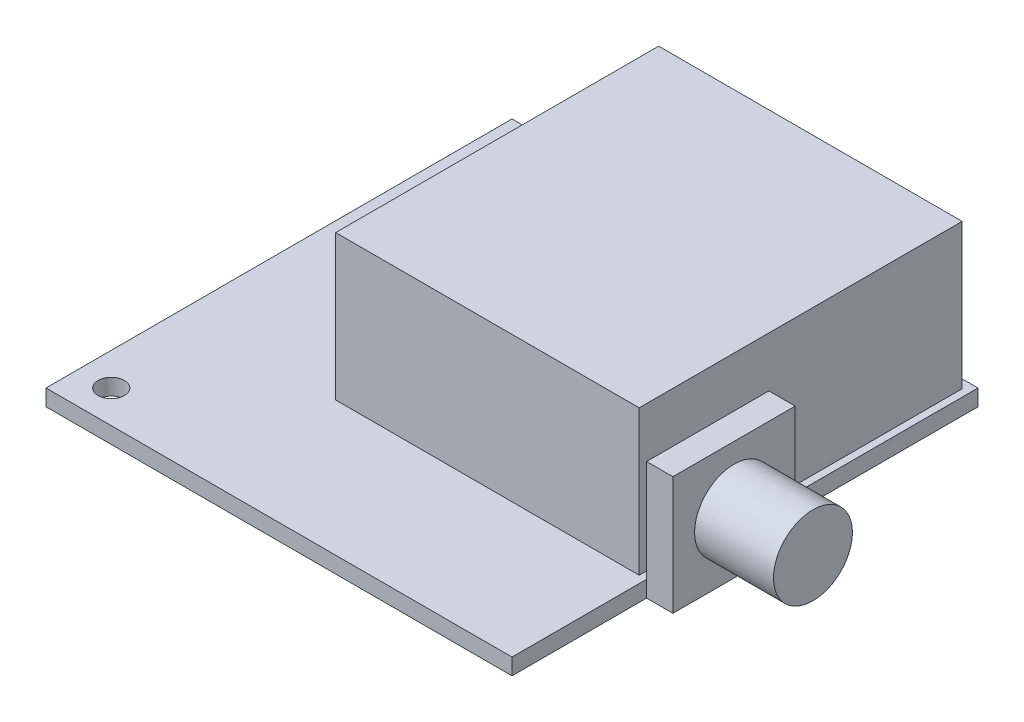
SolidWorks part; units mm, degrees
ref_plane "Front Plane" through (0, 0, 0) normal (0, 0, 1) x (1, 0, 0)
ref_plane "Top Plane" through (0, 0, 0) normal (0, 1, 0) x (1, 0, 0)
ref_plane "Right Plane" through (0, 0, 0) normal (1, 0, 0) x (0, 0, -1)
sketch "Sketch1" plane through (0, 0, 0) normal (0, 1, 0) x (1, 0, 0)
  line L1 (-22.5, 22.5) -> (22.5, 22.5)
  line L2 (-22.5, 22.5) -> (-22.5, -22.5)
  line L3 (-22.5, -22.5) -> (22.5, -22.5)
  line L4 (22.5, 22.5) -> (22.5, -22.5)
  circle A0 centre (-19.3504, 19.3504) radius 1.27
  circle A1 centre (-19.3504, -19.3504) radius 1.27
  point P4 (0, 22.5)
  point P6 (-22.5, 0)
  dimension "D3" = 3.1496
  dimension "D7" = 2.54
  dimension "D8" = 2.54
  dimension "D1" = 45
  dimension "D2" = 45
  dimension "D4" = 3.1496
  dimension "D5" = 3.1496
  dimension "D6" = 3.1496
extrude "Boss-Extrude1" add sketch "Sketch1" along normal blind 1.5748
sketch "Sketch2" plane through (0, 1.5748, 0) normal (0, 1, 0) x (1, 0, 0)
  line L1 (21.7985, 21.6681) -> (-7.5095, 21.6681)
  line L2 (21.7985, 21.6681) -> (21.7985, -9.5173)
  line L3 (21.7985, -9.5173) -> (-7.5095, -9.5173)
  line L4 (-7.5095, 21.6681) -> (-7.5095, -9.5173)
extrude "Boss-Extrude2" add sketch "Sketch2" along normal blind 14
sketch "Sketch3" plane through (22.5, 0, 0) normal (1, 0, 0) x (0, 0, -1)
  line L0 (-22.5, 0) -> (22.5, 0) construction
  line L1 (-9.5031, 0) -> (2.3063, 0)
  line L2 (-9.5031, 0) -> (-9.5031, 11.4281)
  line L3 (-9.5031, 11.4281) -> (2.3063, 11.4281)
  line L4 (2.3063, 0) -> (2.3063, 11.4281)
extrude "Boss-Extrude3" add sketch "Sketch3" along normal blind 2.54
sketch "Sketch4" plane through (25.04, 0, 0) normal (1, 0, 0) x (0, 0, -1)
  line L0 (2.3063, 11.4281) -> (-9.5031, 11.4281) construction
  line L1 (-9.5031, 11.4281) -> (-9.5031, 0) construction
  circle A0 centre (-3.5984, 5.714) radius 3.81
  point P4 (-3.5984, 11.4281)
  point P7 (-9.5031, 5.714)
  dimension "D1" = 7.62
extrude "Boss-Extrude4" add sketch "Sketch4" along normal blind 7.62
